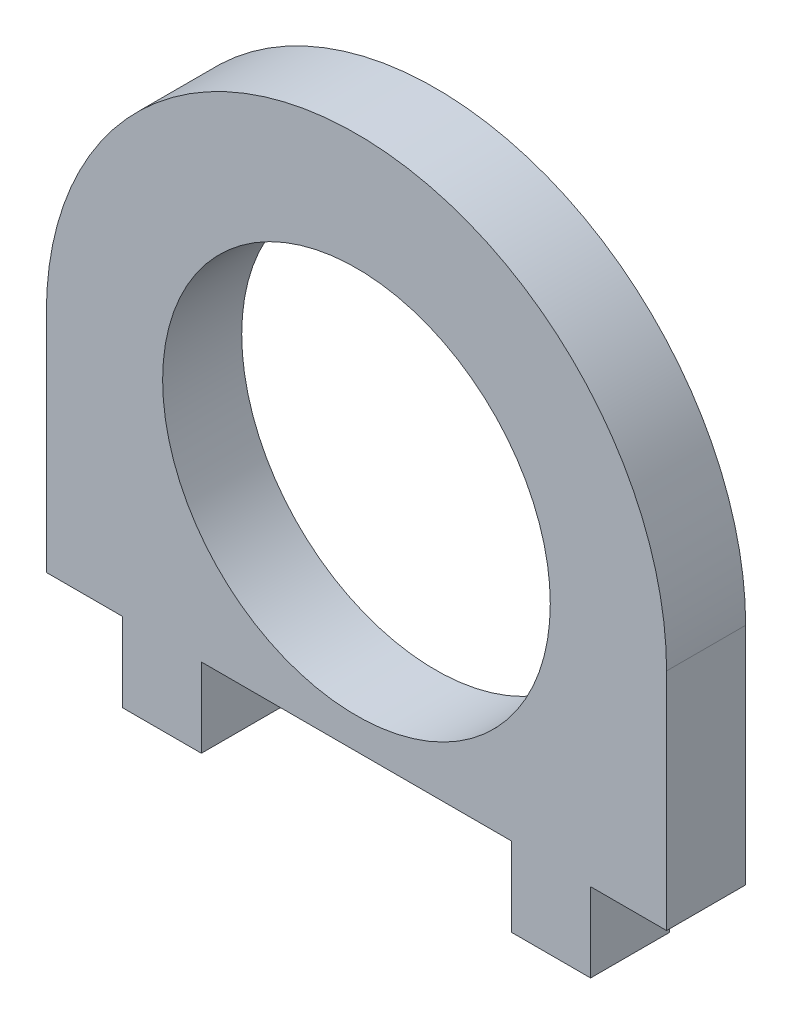
SolidWorks part; units mm, degrees
ref_plane "Front Plane" through (0, 0, 0) normal (0, 0, 1) x (1, 0, 0)
ref_plane "Top Plane" through (0, 0, 0) normal (0, 1, 0) x (1, 0, 0)
ref_plane "Right Plane" through (0, 0, 0) normal (1, 0, 0) x (0, 0, -1)
sketch "Sketch1" plane through (0, 0, 0) normal (0, 0, 1) x (1, 0, 0)
  line L0 (-44.3755, 2) -> (12.5836, 2) construction
  line L1 (0, 0) -> (-4.9, 0)
  line L2 (0, 0) -> (0, 14.5)
  line L4 (-40, 0) -> (-40, 14.5)
  line L6 (-35.1, 0) -> (-35.1, -5.1)
  line L7 (-35.1, -5.1) -> (-30, -5.1)
  line L8 (-30, 0) -> (-30, -5.1)
  line L10 (-10, 0) -> (-10, -5.1)
  line L11 (-10, -5.1) -> (-4.9, -5.1)
  line L12 (-4.9, 0) -> (-4.9, -5.1)
  line L13 (-10, 0) -> (-30, 0)
  line L14 (-35.1, 0) -> (-40, 0)
  circle A0 centre (-20, 14.5) radius 12.5
  arc A2 (0, 14.5) -> (-40, 14.5) centre (-20, 14.5) ccw
  dimension "D10" = 25
  dimension "D7" = 20
  dimension "D1" = 5.1
  dimension "D2" = 5.1
  dimension "D3" = 5.1
  dimension "D4" = 5.1
  dimension "D5" = 20
  dimension "D6" = 10
  dimension "D8" = 40
  dimension "D9" = 2
extrude "Boss-Extrude1" add sketch "Sketch1" along normal blind 5.1
